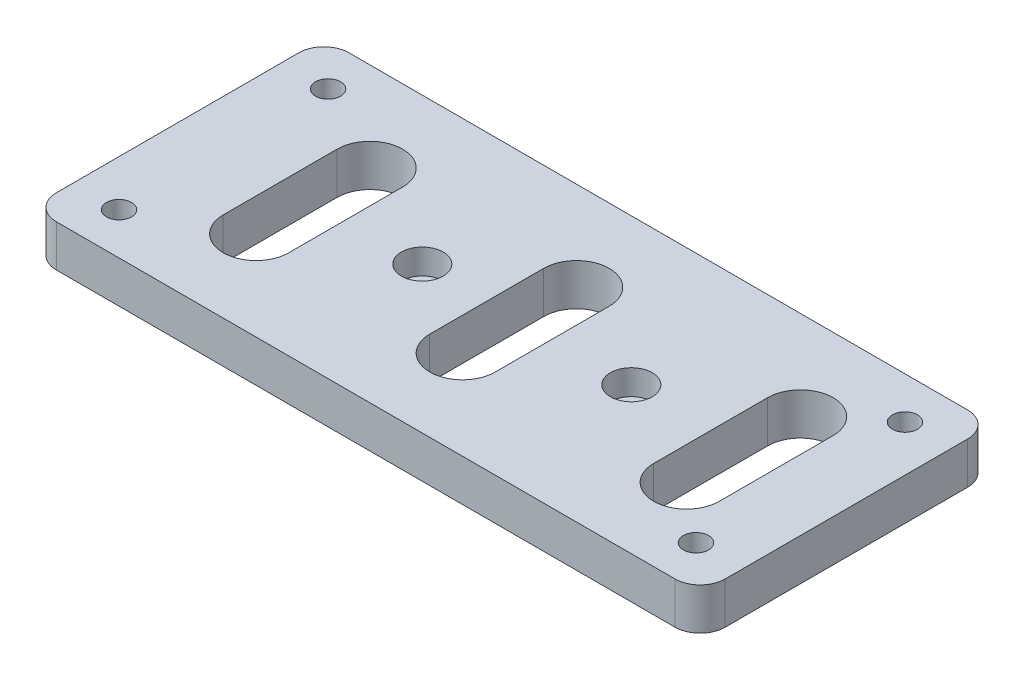
SolidWorks part; units mm, degrees
ref_plane "Plan de face" through (0, 0, 0) normal (0, 0, 1) x (1, 0, 0)
ref_plane "Plan de dessus" through (0, 0, 0) normal (0, 1, 0) x (1, 0, 0)
ref_plane "Plan de droite" through (0, 0, 0) normal (1, 0, 0) x (0, 0, -1)
sketch "Esquisse1" plane through (0, 0, 0) normal (0, 1, 0) x (1, 0, 0)
  line L1 (0, 0) -> (80, 0)
  line L2 (0, 0) -> (0, 35)
  line L3 (0, 35) -> (80, 35)
  line L4 (80, 0) -> (80, 35)
  dimension "D1" = 80
  dimension "D2" = 35
extrude "Boss.-Extru.1" add sketch "Esquisse1" along normal blind 5
sketch "Esquisse2" plane through (0, 5, 0) normal (0, 1, 0) x (1, 0, 0)
  line L0 (54.2705, 17.5) -> (66.7705, 17.5) construction
  line L1 (29.2705, 17.5) -> (6.7705, 17.5) construction
  line L2 (0, 35) -> (0, 0) construction
  line L5 (80, 35) -> (0, 35) construction
  line L6 (80, 0) -> (80, 35) construction
  line L8 (67.6804, 24.3104) -> (67.6804, 10.6896) construction
  line L9 (71.6025, 24.3104) -> (71.6025, 10.6896)
  line L10 (63.7584, 24.3104) -> (63.7584, 10.6896)
  line L11 (40.8937, 24.3104) -> (40.8937, 10.6896) construction
  line L14 (44.8157, 24.3104) -> (44.8157, 10.6896)
  line L15 (36.9716, 24.3104) -> (36.9716, 10.6896)
  line L16 (16.1931, 24.3104) -> (16.1931, 10.6896) construction
  line L17 (20.1151, 24.3104) -> (20.1151, 10.6896)
  line L18 (12.271, 24.3104) -> (12.271, 10.6896)
  circle A0 centre (5.5, 30) radius 1.5
  circle A3 centre (74.5, 30) radius 1.5
  circle A4 centre (29.2705, 17.5) radius 1.3
  circle A7 centre (54.2705, 17.5) radius 1.3
  circle A8 centre (74.5, 5) radius 1.5
  circle A9 centre (5.5, 5) radius 1.5
  arc A10 (71.6025, 24.3104) -> (63.7584, 24.3104) centre (67.6804, 24.3104) ccw
  arc A11 (63.7584, 10.6896) -> (71.6025, 10.6896) centre (67.6804, 10.6896) ccw
  arc A14 (44.8157, 24.3104) -> (36.9716, 24.3104) centre (40.8937, 24.3104) ccw
  arc A15 (36.9716, 10.6896) -> (44.8157, 10.6896) centre (40.8937, 10.6896) ccw
  arc A16 (20.1151, 24.3104) -> (12.271, 24.3104) centre (16.1931, 24.3104) ccw
  arc A17 (12.271, 10.6896) -> (20.1151, 10.6896) centre (16.1931, 10.6896) ccw
  point P5 (0, 17.5)
  point P8 (67.6804, 17.5)
  point P28 (0, 0)
  point P29 (0, 0)
  point P30 (64.426, 27.2311)
  point P31 (67.6804, 24.3104)
  point P32 (40.8937, 17.5)
  point P39 (16.1931, 17.5)
  point P46 (0, 0)
  dimension "D5" = 3
  dimension "D6" = 2.6
  dimension "D1" = 25
  dimension "D2" = 12.5
  dimension "D3" = 22.5
  dimension "D4" = 25
  dimension "D7" = 69
  dimension "D8" = 5
  dimension "D9" = 5.5
extrude "Enlèv. mat.-Extru.1" cut sketch "Esquisse2" against normal through all
sketch "Esquisse4" plane through (0, 5, 0) normal (0, 1, 0) x (1, 0, 0)
  circle A0 centre (29.2705, 17.5) radius 2.5
  circle A3 centre (54.2705, 17.5) radius 2.5
  dimension "D1" = 5
extrude "Enlèv. mat.-Extru.2" cut sketch "Esquisse4" against normal blind 3
fillet "Congé1" radius 3 4 edges at (80, 2.5, 0) (80, 2.5, -35) (0, 2.5, -35) (0, 2.5, 0)
